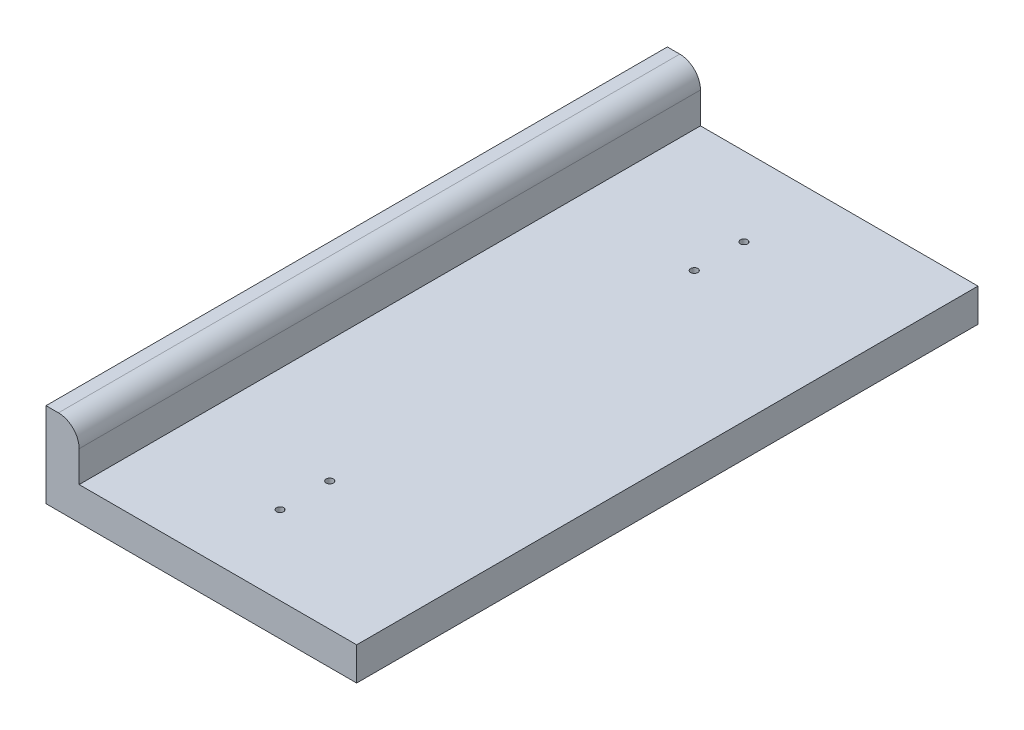
SolidWorks part; units mm, degrees
ref_plane "Front Plane" through (0, 0, 0) normal (0, 0, 1) x (1, 0, 0)
ref_plane "Top Plane" through (0, 0, 0) normal (0, 1, 0) x (1, 0, 0)
ref_plane "Right Plane" through (0, 0, 0) normal (1, 0, 0) x (0, 0, -1)
other "Bounding Box"
ref_plane "Default Plane" through (-75, 41, 150) normal (1, 0, 0) x (0, 0, -1)
sketch "Sketch1" plane through (0, 0, 0) normal (0, 1, 0) x (1, 0, 0)
  line L1 (-75, -150) -> (75, -150)
  line L2 (-75, -150) -> (-75, 150)
  line L3 (-75, 150) -> (75, 150)
  line L4 (75, -150) -> (75, 150)
  line L5 (-75, -150) -> (75, 150) construction
  line L6 (-75, 150) -> (75, -150) construction
  point P0 (0, 0)
  dimension "D1" = 150
  dimension "D2" = 300
extrude "Boss-Extrude1" add sketch "Sketch1" along normal blind 16
sketch "Sketch2" plane through (0, 16, 0) normal (0, 1, 0) x (1, 0, 0)
  line L0 (-75, -150) -> (75, -150) construction
  line L1 (-75, 150) -> (-59, 150)
  line L2 (-75, 150) -> (-75, -150)
  line L3 (-75, -150) -> (-59, -150)
  line L4 (-59, 150) -> (-59, -150)
  line L5 (75, 150) -> (-75, 150) construction
  line L6 (75, -150) -> (59, -150) construction
  line L7 (75, -150) -> (75, 150) construction
  line L8 (75, 150) -> (59, 150) construction
  line L9 (59, -150) -> (59, 150) construction
  dimension "D1" = 16
extrude "Boss-Extrude2" add sketch "Sketch2" along normal blind 25
fillet "Fillet1" radius 10 1 edges at (-59, 41, 0)
hole_wizard "#8-36 Tapped Hole1" positions "Sketch5" profile "Sketch4" tap size "#8-36" standard "ANSI Inch" end condition through all
sketch "Sketch5" plane through (0, 0, 0) normal (0, -1, 0) x (-1, 0, 0)
  line L0 (0, 112) -> (0, 88) construction
  line L2 (-75, 150) -> (75, 150) construction
  point P0 (0, 112)
  point P2 (0, 88)
  point P10 (0, 100)
  dimension "D1" = 24
  dimension "D2" = 50
sketch "Sketch4" plane through (0, 0, -112) normal (1, 0, 0) x (0, 0, -1)
  line L0 (0, 0) -> (0, 41)
  line L1 (0, 41) -> (1.7272, 41)
  line L2 (1.7272, 41) -> (1.7272, 0)
  line L5 (1.7272, 0) -> (0, 0)
  line L11 (0, -6.35) -> (0, 107.95) construction
  dimension "Thru Tap Drill Dia." = 3.4544
  dimension "Thru Tap Drill Depth" = 41
cosmetic thread "Hole Thread1" parameters "D2"=4.1656
cosmetic thread "Hole Thread2" parameters "D2"=4.1656
mirror "Mirror1" about plane through (0, 0, 0) normal (0, 0, 1) of "#8-36 Tapped Hole1"
cosmetic thread "Hole Thread3" parameters "D2"=4.1656
cosmetic thread "Hole Thread4" parameters "D2"=4.1656
